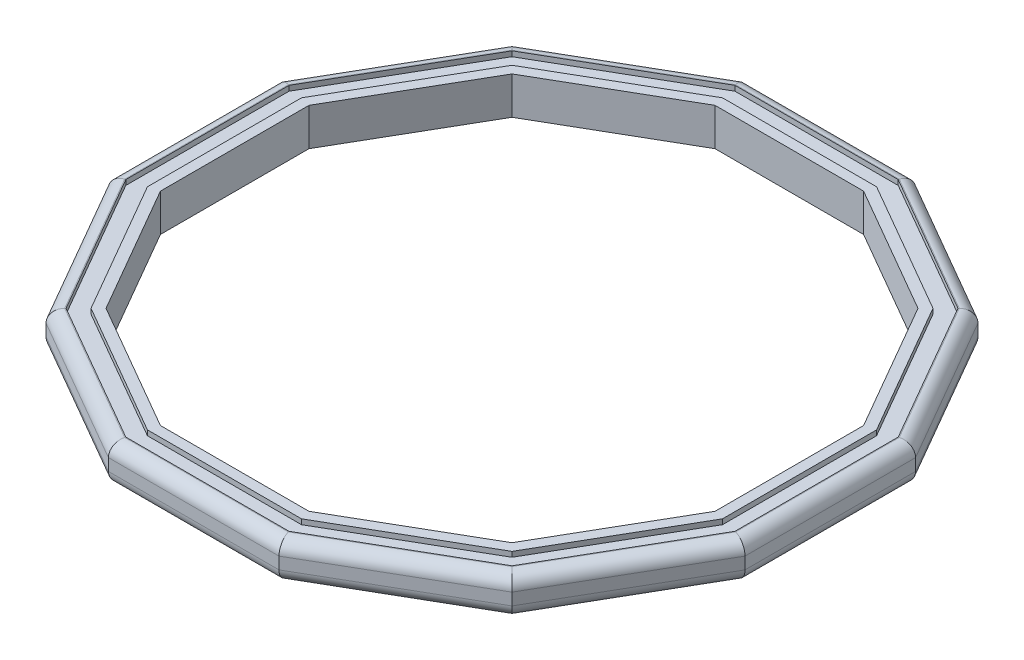
SolidWorks part; units mm, degrees
ref_plane "정면" through (0, 0, 0) normal (0, 0, 1) x (1, 0, 0)
ref_plane "윗면" through (0, 0, 0) normal (0, 1, 0) x (1, 0, 0)
ref_plane "우측면" through (0, 0, 0) normal (1, 0, 0) x (0, 0, -1)
sketch "스케치1" plane through (0, 0, 0) normal (0, 1, 0) x (1, 0, 0)
  line L1 (27.2932, -27.2932) -> (37.2832, -9.99)
  line L2 (37.2832, -9.99) -> (37.2832, 9.99)
  line L3 (37.2832, 9.99) -> (27.2932, 27.2932)
  line L4 (27.2932, 27.2932) -> (9.99, 37.2832)
  line L5 (9.99, 37.2832) -> (-9.99, 37.2832)
  line L6 (-9.99, 37.2832) -> (-27.2932, 27.2932)
  line L7 (-27.2932, 27.2932) -> (-37.2832, 9.99)
  line L8 (-37.2832, 9.99) -> (-37.2832, -9.99)
  line L9 (-37.2832, -9.99) -> (-27.2932, -27.2932)
  line L10 (-27.2932, -27.2932) -> (-9.99, -37.2832)
  line L11 (-9.99, -37.2832) -> (9.99, -37.2832)
  line L12 (9.99, -37.2832) -> (27.2932, -27.2932)
  circle A0 centre (0, 0) radius 37.2832 construction
  dimension "D1" = 19.98
extrude "보스-돌출1" add sketch "스케치1" along normal blind 4.4
sketch "스케치2" plane through (0, 4.4, 0) normal (0, 1, 0) x (1, 0, 0)
  line L0 (-26.1209, 26.1209) -> (-35.6818, 9.5609)
  line L1 (24.6568, -24.6568) -> (33.6818, -9.025)
  line L2 (33.6818, -9.025) -> (33.6818, 9.025)
  line L3 (33.6818, 9.025) -> (24.6568, 24.6568)
  line L4 (24.6568, 24.6568) -> (9.025, 33.6818)
  line L5 (9.025, 33.6818) -> (-9.025, 33.6818)
  line L6 (-9.025, 33.6818) -> (-24.6568, 24.6568)
  line L7 (-24.6568, 24.6568) -> (-33.6818, 9.025)
  line L8 (-33.6818, 9.025) -> (-33.6818, -9.025)
  line L9 (-33.6818, -9.025) -> (-24.6568, -24.6568)
  line L10 (-24.6568, -24.6568) -> (-9.025, -33.6818)
  line L11 (-9.025, -33.6818) -> (9.025, -33.6818)
  line L12 (9.025, -33.6818) -> (24.6568, -24.6568)
  line L13 (-35.6818, 9.5609) -> (-35.6818, -9.5609)
  line L14 (-35.6818, -9.5609) -> (-26.1209, -26.1209)
  line L15 (-26.1209, -26.1209) -> (-9.5609, -35.6818)
  line L16 (-9.5609, -35.6818) -> (9.5609, -35.6818)
  line L17 (9.5609, -35.6818) -> (26.1209, -26.1209)
  line L18 (26.1209, -26.1209) -> (35.6818, -9.5609)
  line L19 (35.6818, -9.5609) -> (35.6818, 9.5609)
  line L20 (35.6818, 9.5609) -> (26.1209, 26.1209)
  line L21 (26.1209, 26.1209) -> (9.5609, 35.6818)
  line L22 (9.5609, 35.6818) -> (-9.5609, 35.6818)
  line L23 (-9.5609, 35.6818) -> (-26.1209, 26.1209)
  circle A0 centre (0, 0) radius 33.6818 construction
  dimension "D1" = 18.05
  dimension "D2" = 2
extrude "컷-돌출1" cut sketch "스케치2" against normal blind 0.6
fillet "필렛1" radius 1.5 24 edges at (-32.2882, 0, 18.6416) (-37.2832, 0, 0) (-32.2882, 0, -18.6416) (-18.6416, 0, -32.2882) (0, 0, -37.2832) (18.6416, 0, -32.2882) (32.2882, 0, -18.6416) (-32.2882, 4.4, 18.6416) (-37.2832, 4.4, 0) (-32.2882, 4.4, -18.6416) (-18.6416, 4.4, -32.2882) (0, 4.4, -37.2832) (18.6416, 4.4, -32.2882) (32.2882, 4.4, -18.6416) (37.2832, 4.4, 0) (37.2832, 0, 0) (32.2882, 4.4, 18.6416) (32.2882, 0, 18.6416) (18.6416, 0, 32.2882) (18.6416, 4.4, 32.2882) (0, 0, 37.2832) (0, 4.4, 37.2832) (-18.6416, 0, 32.2882) (-18.6416, 4.4, 32.2882)
sketch "스케치3" plane through (0, 4.4, 0) normal (0, 1, 0) x (1, 0, 0)
  line L0 (-8.7035, 32.4818) -> (-23.7783, 23.7783)
  line L1 (-23.7783, 23.7783) -> (-32.4818, 8.7035)
  line L2 (-32.4818, 8.7035) -> (-32.4818, -8.7035)
  line L3 (-32.4818, -8.7035) -> (-23.7783, -23.7783)
  line L4 (-23.7783, -23.7783) -> (-8.7035, -32.4818)
  line L5 (-8.7035, -32.4818) -> (8.7035, -32.4818)
  line L6 (8.7035, -32.4818) -> (23.7783, -23.7783)
  line L7 (23.7783, -23.7783) -> (32.4818, -8.7035)
  line L8 (32.4818, -8.7035) -> (32.4818, 8.7035)
  line L9 (32.4818, 8.7035) -> (23.7783, 23.7783)
  line L10 (23.7783, 23.7783) -> (8.7035, 32.4818)
  line L11 (8.7035, 32.4818) -> (-8.7035, 32.4818)
  line L12 (-9.025, -33.6818) -> (9.025, -33.6818)
  line L13 (9.025, -33.6818) -> (24.6568, -24.6568)
  line L14 (24.6568, -24.6568) -> (33.6818, -9.025)
  line L15 (33.6818, -9.025) -> (33.6818, 9.025)
  line L16 (33.6818, 9.025) -> (24.6568, 24.6568)
  line L17 (24.6568, 24.6568) -> (9.025, 33.6818)
  line L18 (9.025, 33.6818) -> (-9.025, 33.6818)
  line L19 (-9.025, 33.6818) -> (-24.6568, 24.6568)
  line L20 (-24.6568, 24.6568) -> (-33.6818, 9.025)
  line L21 (-33.6818, 9.025) -> (-33.6818, -9.025)
  line L22 (-33.6818, -9.025) -> (-24.6568, -24.6568)
  line L23 (-24.6568, -24.6568) -> (-9.025, -33.6818)
  line L24 (-9.025, -33.6818) -> (9.025, -33.6818)
  line L25 (9.025, -33.6818) -> (24.6568, -24.6568)
  line L26 (24.6568, -24.6568) -> (33.6818, -9.025)
  line L27 (33.6818, -9.025) -> (33.6818, 9.025)
  line L28 (33.6818, 9.025) -> (24.6568, 24.6568)
  line L29 (24.6568, 24.6568) -> (9.025, 33.6818)
  line L30 (9.025, 33.6818) -> (-9.025, 33.6818)
  line L31 (-9.025, 33.6818) -> (-24.6568, 24.6568)
  line L32 (-24.6568, 24.6568) -> (-33.6818, 9.025)
  line L33 (-33.6818, 9.025) -> (-33.6818, -9.025)
  line L34 (-33.6818, -9.025) -> (-24.6568, -24.6568)
  line L35 (-24.6568, -24.6568) -> (-9.025, -33.6818)
  dimension "D1" = 0
  dimension "D2" = 1.2
extrude "컷-돌출2" cut sketch "스케치3" against normal through all both contours L10 L11 L0 L1 L2 L3 L4 L5 L6 L7 L8 L9
ref_plane "평면1" through (0, 2.2, 0) normal (0, 1, 0) x (1, 0, 0)
mirror "대칭 복사1" about plane through (0, 2.2, 0) normal (0, 1, 0) of "컷-돌출1"
